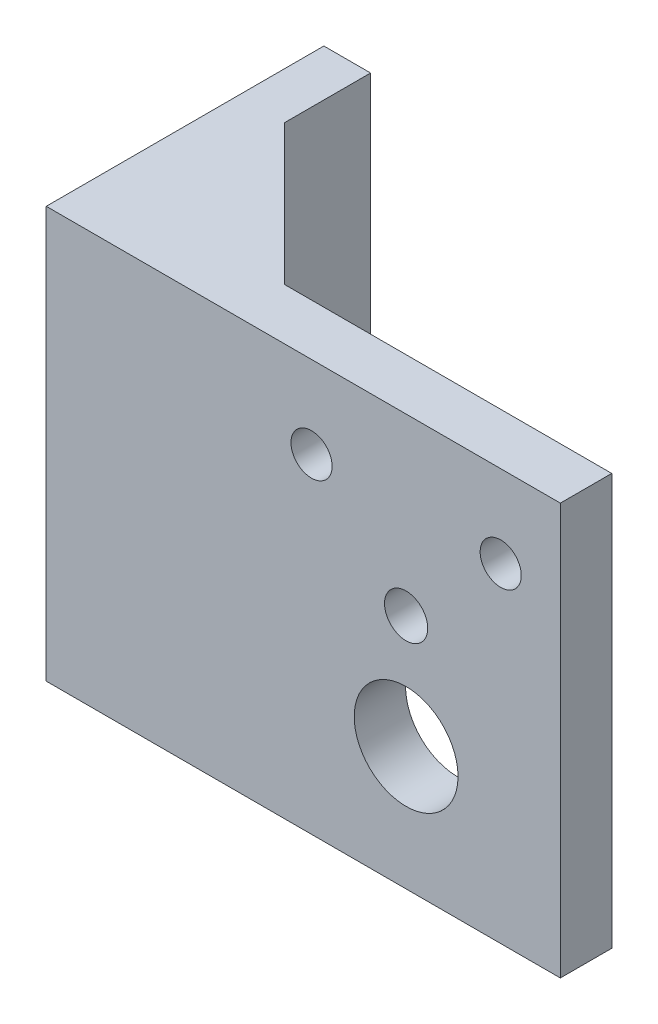
SolidWorks part; units mm, degrees
ref_plane "Front Plane" through (0, 0, 0) normal (0, 0, 1) x (1, 0, 0)
ref_plane "Top Plane" through (0, 0, 0) normal (0, 1, 0) x (1, 0, 0)
ref_plane "Right Plane" through (0, 0, 0) normal (1, 0, 0) x (0, 0, -1)
sketch "Sketch1" plane through (0, 0, 0) normal (0, 1, 0) x (1, 0, 0)
  line L7 (0, 0) -> (50, 0)
  line L8 (50, 0) -> (50, 5)
  line L9 (50, 5) -> (18.1818, 5)
  line L10 (4.5455, 18.6364) -> (4.5455, 35)
  line L11 (4.5455, 35) -> (0, 35)
  line L12 (0, 35) -> (0, 0)
  line L13 (4.5455, 18.6364) -> (18.1818, 5)
  dimension "D1" = 50
  dimension "D2" = 35
  dimension "D3" = 5
extrude "Boss-Extrude1" add sketch "Sketch1" along normal blind 40 contours L8 L9 L13 L10 L11 L12 L7
sketch "Sketch3" plane through (0, 0, 0) normal (0, -1, 0) x (1, 0, 0)
  line L0 (4.5455, -18.6364) -> (4.5455, -5)
  line L1 (4.5455, -5) -> (18.1818, -5)
  line L2 (4.5455, -18.6364) -> (18.1818, -5)
extrude "Cut-Extrude1" cut sketch "Sketch3" against normal blind 35 contours L2 L1 L0
sketch "Sketch5" plane through (0, 0, 0) normal (0, -1, 0) x (1, 0, 0)
  line L0 (4.5455, -20) -> (4.5455, -5)
  line L1 (4.5455, -5) -> (4.5455, -35) construction
  line L2 (4.5455, -5) -> (20, -5)
  line L3 (50, -5) -> (4.5455, -5) construction
  line L4 (20, -5) -> (4.5455, -20)
extrude "Boss-Extrude2" add sketch "Sketch5" against normal blind 5 contours L4 L0 L2
sketch "Sketch6" plane through (4.5455, 0, 0) normal (1, 0, 0) x (0, 0, -1)
  line L0 (13, 30) -> (13, 10) construction
  line L2 (13, 20) -> (21, 20) construction
  line L3 (5, 35) -> (5, 5) construction
  circle A2 centre (13, 30) radius 2
  circle A4 centre (13, 10) radius 2
  circle A5 centre (21, 20) radius 2
  dimension "D1" = 4
  dimension "D2" = 8
  dimension "D3" = 8
  dimension "D7" = 20
extrude "Cut-Extrude2" cut sketch "Sketch6" against normal through all
sketch "Sketch7" plane through (0, 0, -5) normal (0, 0, -1) x (-1, 0, 0)
  line L0 (-50, 0) -> (-20, 0) construction
  line L2 (-50, 40) -> (-50, 0) construction
  line L4 (-50, 40) -> (-18.1818, 40) construction
  circle A0 centre (-35, 12) radius 3.1
  circle A1 centre (-35, 23) radius 2.1
  circle A2 centre (-25.8, 32) radius 2
  circle A3 centre (-44.2, 32) radius 2
  dimension "D1" = 12
  dimension "D2" = 15
  dimension "D3" = 11
  dimension "D4" = 5.8
  dimension "D5" = 8
  dimension "D6" = 18.4
  dimension "D7" = 15
extrude "Cut-Extrude4" cut sketch "Sketch7" against normal through all
sketch "Sketch8" plane through (0, 0, 0) normal (0, 0, 1) x (1, 0, 0)
  circle A0 centre (35, 12) radius 5.05
extrude "Cut-Extrude5" cut sketch "Sketch8" against normal through all
sketch "Sketch10" plane through (4.5455, 0, 0) normal (1, 0, 0) x (0, 0, -1)
  line L0 (20, 0) -> (35, 0) construction
  line L1 (35, 40) -> (27, 40)
  line L2 (35, 40) -> (35, 0)
  line L3 (35, 0) -> (27, 0)
  line L4 (27, 40) -> (27, 0)
  dimension "D1" = 8
extrude "Cut-Extrude8" cut sketch "Sketch10" against normal through all
